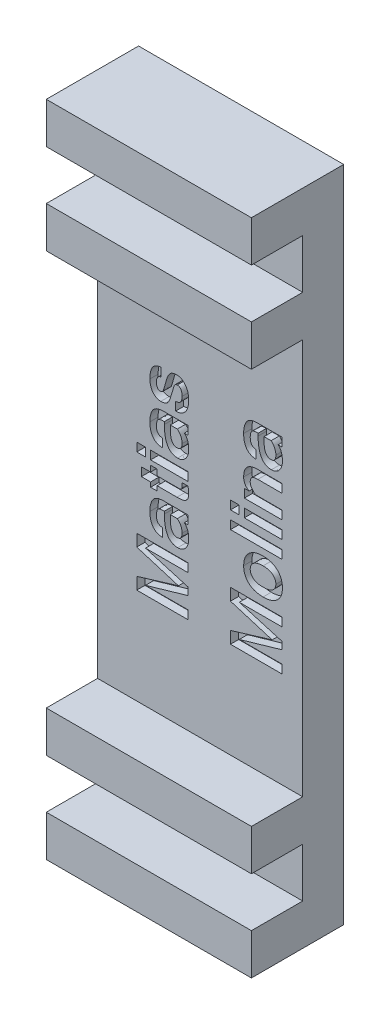
SolidWorks part; units mm, degrees
ref_plane "Alzado" through (0, 0, 0) normal (1, 0, 0) x (0, 1, 0)
ref_plane "Planta" through (0, 0, 0) normal (0, 0, 1) x (0, 1, 0)
ref_plane "Vista lateral" through (0, 0, 0) normal (0, 1, 0) x (-1, 0, 0)
sketch "Croquis1" plane through (0, 0, 0) normal (0, 0, 1) x (0, 1, 0)
  line L1 (-32.1, 10) -> (32.1, 10)
  line L2 (-32.1, 10) -> (-32.1, -10)
  line L3 (-32.1, -10) -> (32.1, -10)
  line L4 (32.1, 10) -> (32.1, -10)
  line L5 (-32.1, 10) -> (32.1, -10) construction
  line L6 (-32.1, -10) -> (32.1, 10) construction
  point P0 (0, 0)
  dimension "D1" = 64.2
  dimension "D2" = 20
extrude "Saliente-Extruir1" add sketch "Croquis1" along normal blind 4
sketch "Croquis2" plane through (0, 0, 4) normal (0, 0, 1) x (1, 0, 0)
  line L0 (10, -32.1) -> (10, 32.1) construction
  line L1 (-10, 32.1) -> (10, 32.1)
  line L2 (-10, 32.1) -> (-10, 28.1)
  line L3 (-10, 28.1) -> (10, 28.1)
  line L4 (10, 32.1) -> (10, 28.1)
  line L5 (-10, 32.1) -> (-10, -32.1) construction
  line L6 (-10, 19.3) -> (10, 19.3)
  line L7 (-10, 19.3) -> (-10, 23.3)
  line L8 (-10, 23.3) -> (10, 23.3)
  line L9 (10, 19.3) -> (10, 23.3)
  line L10 (-10, 0) -> (10, 0) construction
  line L11 (10, -19.3) -> (10, -23.3)
  line L12 (-10, -23.3) -> (10, -23.3)
  line L13 (-10, -19.3) -> (-10, -23.3)
  line L14 (-10, -19.3) -> (10, -19.3)
  line L15 (10, -32.1) -> (10, -28.1)
  line L16 (-10, -28.1) -> (10, -28.1)
  line L17 (-10, -32.1) -> (-10, -28.1)
  line L18 (-10, -32.1) -> (10, -32.1)
  dimension "D1" = 23.3
  dimension "D2" = 4
  dimension "D3" = 4.8
extrude "Saliente-Extruir2" add sketch "Croquis2" along normal blind 5
sketch "Croquis3" plane through (0, 0, 4) normal (0, 0, 1) x (1, 0, 0)
  text T0 "\r\nMatias\r\nMolina" font "Microsoft Sans Serif" height 5
extrude "Cortar-Extruir1" cut sketch "Croquis3" against normal blind 0.8
